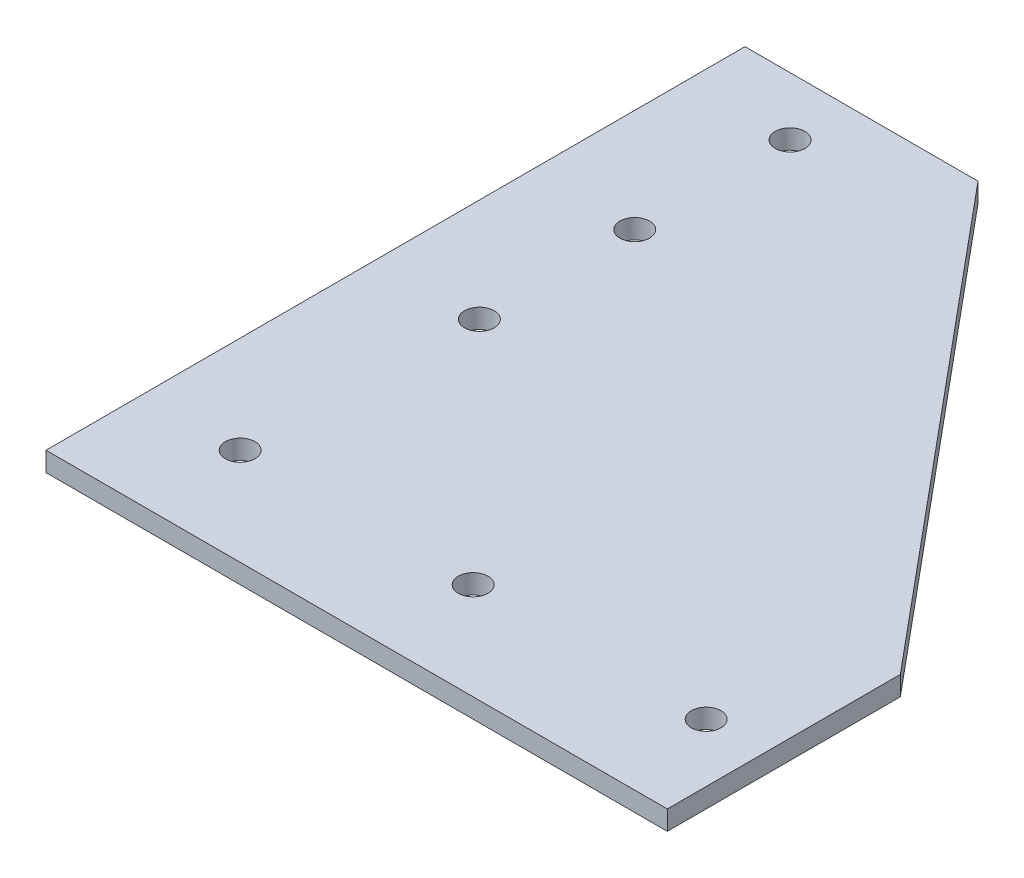
SolidWorks part; units mm, degrees
material "5052-H32"
ref_plane "Front" through (0, 0, 0) normal (0, 0, 1) x (1, 0, 0)
ref_plane "Top" through (0, 0, 0) normal (0, 1, 0) x (1, 0, 0)
ref_plane "Right" through (0, 0, 0) normal (1, 0, 0) x (0, 0, -1)
sketch "Sketch1" plane through (0, 0, 0) normal (0, 1, 0) x (1, 0, 0)
  line L0 (0, 0) -> (0, 114.3)
  line L1 (0, 114.3) -> (38.1, 114.3)
  line L2 (38.1, 114.3) -> (101.6, 38.1)
  line L3 (101.6, 38.1) -> (101.6, 0)
  line L4 (101.6, 0) -> (0, 0)
  circle A0 centre (15.875, 15.875) radius 2.4257
  circle A1 centre (53.975, 15.875) radius 2.4257
  circle A2 centre (92.075, 15.875) radius 2.4257
  circle A3 centre (16.891, 53.975) radius 2.4257
  circle A4 centre (16.891, 79.375) radius 2.4257
  circle A5 centre (16.891, 104.775) radius 2.4257
  dimension "D1" = 4.8514
  dimension "D2" = 15.875
  dimension "D3" = 15.875
  dimension "D5" = 38.1
  dimension "D6" = 53.975
  dimension "D7" = 16.891
  dimension "D9" = 38.1
  dimension "D10" = 38.1
  dimension "D11" = 101.6
  dimension "D12" = 114.3
  dimension "D13" = 25.4
  dimension "D4" = 3
  dimension "D8" = 3
extrude "Boss-Extrude1" add sketch "Sketch1" along normal blind 3.175
fillet "Fillet1" [suppressed] radius 3.175
sketch "Sketch2" plane through (0, 0, 0) normal (0, -1, 0) x (1, 0, 0)
  line L0 (0, -114.3) -> (0, 0) construction
  line L1 (0, 0) -> (101.6, 0) construction
  circle A0 centre (50.8, -50.8) radius 4.3688
  dimension "D1" = 8.7376
  dimension "D2" = 50.8
  dimension "D3" = 50.8
extrude "Cut-Extrude1" [suppressed] cut sketch "Sketch2" against normal through all
